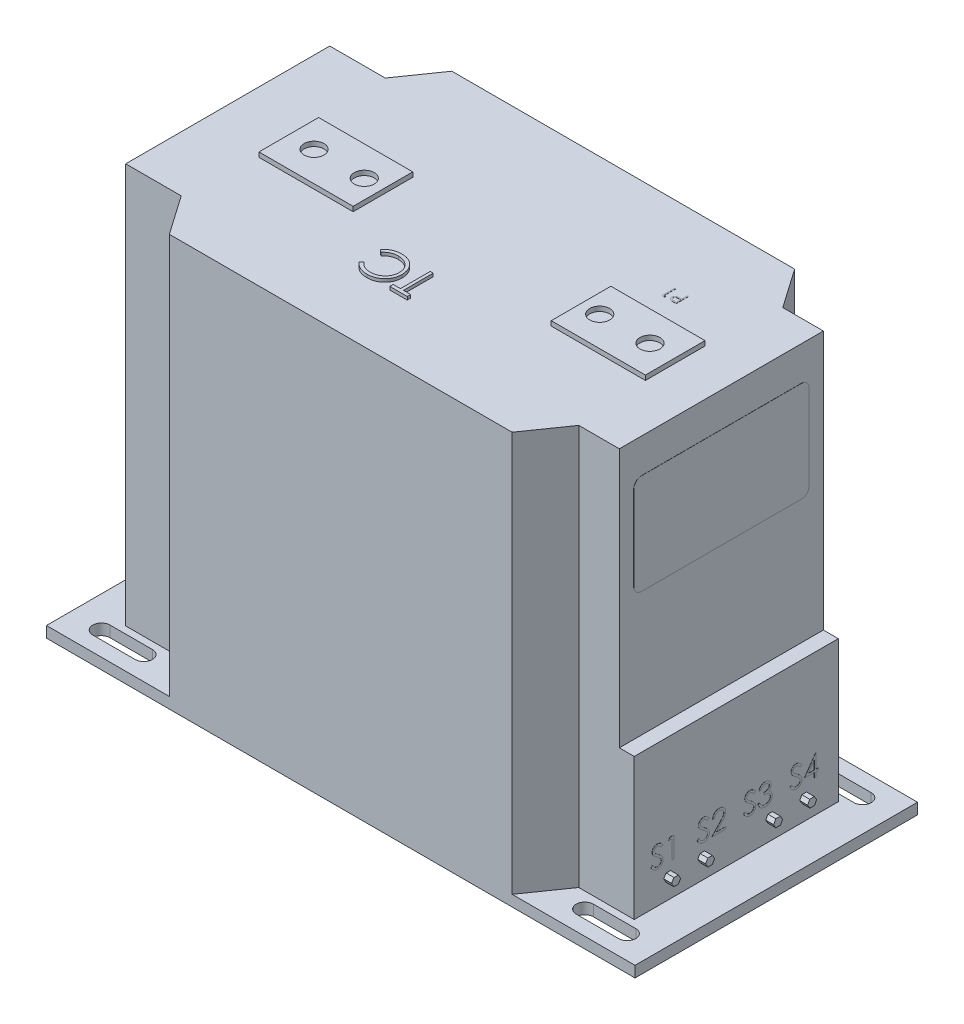
SolidWorks part; units mm, degrees
ref_plane "Alzado" through (0, 0, 0) normal (0, 0, 1) x (1, 0, 0)
ref_plane "Planta" through (0, 0, 0) normal (0, 1, 0) x (1, 0, 0)
ref_plane "Vista lateral" through (0, 0, 0) normal (1, 0, 0) x (0, 0, -1)
sketch "Croquis1" plane through (0, 0, 0) normal (0, 1, 0) x (1, 0, 0)
  line L1 (-187.5, 90) -> (187.5, 90)
  line L2 (-187.5, 90) -> (-187.5, -90)
  line L3 (-187.5, -90) -> (187.5, -90)
  line L4 (187.5, 90) -> (187.5, -90)
  line L5 (-187.5, 90) -> (187.5, -90) construction
  line L6 (-187.5, -90) -> (187.5, 90) construction
  point P0 (0, 0)
  dimension "D1" = 375
  dimension "D2" = 180
extrude "Saliente-Extruir1" add sketch "Croquis1" along normal blind 262
sketch "Croquis2" plane through (0, 262, 0) normal (0, 1, 0) x (1, 0, 0)
  line L0 (0, 0) -> (75, 0) construction
  line L1 (75, 0) -> (107, 0) construction
  line L2 (63.1078, 19) -> (63.1078, -19)
  line L3 (63.1078, -19) -> (123.1078, -19)
  line L4 (123.1078, -19) -> (123.1078, 19)
  line L5 (123.1078, 19) -> (63.1078, 19)
  line L6 (0, 0) -> (0, -29.2326) construction
  line L7 (-75, 0) -> (-107, 0) construction
  line L8 (-123.1078, 19) -> (-63.1078, 19)
  line L9 (-123.1078, -19) -> (-123.1078, 19)
  line L10 (-63.1078, -19) -> (-123.1078, -19)
  line L11 (-63.1078, 19) -> (-63.1078, -19)
  circle A0 centre (75, 0) radius 6.35
  circle A1 centre (107, 0) radius 6.35
  circle A2 centre (-107, 0) radius 6.35
  circle A3 centre (-75, 0) radius 6.35
  dimension "D2" = 12.7
  dimension "D3" = 12.7
  dimension "D1" = 75
  dimension "D4" = 32
  dimension "D5" = 38
  dimension "D6" = 60
  dimension "D7" = 19
extrude "Saliente-Extruir2" add sketch "Croquis2" along normal blind 3
sketch "Croquis3" plane through (0, 262, 0) normal (0, 1, 0) x (1, 0, 0)
  line L0 (0, 0) -> (0, 90) construction
  line L1 (187.5, 90) -> (-187.5, 90) construction
  line L2 (167.5, 75) -> (140.5, 75) construction
  line L3 (167.5, 69.5) -> (140.5, 69.5)
  line L4 (167.5, 80.5) -> (140.5, 80.5)
  line L5 (0, 0) -> (187.5, 0) construction
  line L6 (187.5, -90) -> (187.5, 90) construction
  line L7 (-167.5, 75) -> (-140.5, 75) construction
  line L8 (-167.5, 69.5) -> (-140.5, 69.5)
  line L9 (-167.5, 80.5) -> (-140.5, 80.5)
  line L10 (-167.5, -75) -> (-140.5, -75) construction
  line L11 (-167.5, -69.5) -> (-140.5, -69.5)
  line L12 (-167.5, -80.5) -> (-140.5, -80.5)
  line L13 (167.5, -75) -> (140.5, -75) construction
  line L14 (167.5, -69.5) -> (140.5, -69.5)
  line L15 (167.5, -80.5) -> (140.5, -80.5)
  line L16 (-126.6467, 65) -> (-109.1945, 90)
  line L17 (-162, 65) -> (-126.6467, 65)
  line L18 (-162, 65) -> (-162, -65)
  line L19 (-162, -65) -> (-126.6467, -65)
  line L20 (162, 65) -> (162, -65)
  line L21 (-162, 65) -> (162, -65) construction
  line L22 (-162, -65) -> (162, 65) construction
  line L23 (-126.6467, -65) -> (-109.1945, -90)
  line L24 (-187.5, -90) -> (187.5, -90) construction
  line L25 (126.6467, -65) -> (109.1945, -90)
  line L26 (126.6467, 65) -> (109.1945, 90)
  line L27 (126.6467, 65) -> (162, 65)
  line L28 (126.6467, -65) -> (162, -65)
  arc A0 (167.5, 69.5) -> (167.5, 80.5) centre (167.5, 75) ccw
  arc A1 (140.5, 80.5) -> (140.5, 69.5) centre (140.5, 75) ccw
  arc A2 (-167.5, 69.5) -> (-167.5, 80.5) centre (-167.5, 75) cw
  arc A3 (-140.5, 80.5) -> (-140.5, 69.5) centre (-140.5, 75) cw
  arc A4 (-167.5, -69.5) -> (-167.5, -80.5) centre (-167.5, -75) ccw
  arc A5 (-140.5, -80.5) -> (-140.5, -69.5) centre (-140.5, -75) ccw
  arc A6 (167.5, -69.5) -> (167.5, -80.5) centre (167.5, -75) cw
  arc A7 (140.5, -80.5) -> (140.5, -69.5) centre (140.5, -75) cw
  point P7 (154, 75)
  point P17 (-154, 75)
  point P24 (-154, -75)
  point P31 (154, -75)
  line M16 (187.5, -90) -> (187.5, 90)
  line M17 (187.5, 90) -> (-187.5, 90)
  line M18 (-187.5, 90) -> (-187.5, -90)
  line M19 (-187.5, -90) -> (187.5, -90)
  dimension "D1" = 75
  dimension "D2" = 167.5
  dimension "D3" = 27
  dimension "D4" = 11
  dimension "D5" = 162
  dimension "D6" = 130
extrude "Cortar-Extruir1" cut sketch "Croquis3" against normal blind 255 contours L23 L19 L18 L17 L16 A5 L12 A4 L11 L9 A3 L8 A2 M17 M18 M19 | L28 L25 L26 L27 L20 A1 L4 A0 L3 L15 A7 L14 A6 M19 M16 M17
sketch "Croquis4" plane through (0, 262, 0) normal (0, 1, 0) x (1, 0, 0)
  line L0 (-167.5, 75) -> (-140.5, 75) construction
  line L1 (-167.5, 80.5) -> (-140.5, 80.5)
  line L2 (-167.5, 69.5) -> (-140.5, 69.5)
  line L3 (-167.5, -75) -> (-140.5, -75) construction
  line L4 (-167.5, -69.5) -> (-140.5, -69.5)
  line L5 (-167.5, -80.5) -> (-140.5, -80.5)
  line L6 (140.5, 75) -> (167.5, 75) construction
  line L7 (140.5, 80.5) -> (167.5, 80.5)
  line L8 (140.5, 69.5) -> (167.5, 69.5)
  line L9 (140.5, -75) -> (167.5, -75) construction
  line L10 (140.5, -69.5) -> (167.5, -69.5)
  line L11 (140.5, -80.5) -> (167.5, -80.5)
  arc A0 (-167.5, 80.5) -> (-167.5, 69.5) centre (-167.5, 75) ccw
  arc A1 (-140.5, 69.5) -> (-140.5, 80.5) centre (-140.5, 75) ccw
  arc A2 (-167.5, -69.5) -> (-167.5, -80.5) centre (-167.5, -75) ccw
  arc A3 (-140.5, -80.5) -> (-140.5, -69.5) centre (-140.5, -75) ccw
  arc A4 (140.5, 80.5) -> (140.5, 69.5) centre (140.5, 75) ccw
  arc A5 (167.5, 69.5) -> (167.5, 80.5) centre (167.5, 75) ccw
  arc A6 (140.5, -69.5) -> (140.5, -80.5) centre (140.5, -75) ccw
  arc A7 (167.5, -80.5) -> (167.5, -69.5) centre (167.5, -75) ccw
  point P4 (-154, 75)
  point P13 (-154, -75)
  point P22 (154, 75)
  point P31 (154, -75)
  dimension "D1" = 11
  dimension "D2" = 11
  dimension "D3" = 11
  dimension "D4" = 11
extrude "Cortar-Extruir2" cut sketch "Croquis4" against normal blind 277
sketch "Croquis5" plane through (162, 0, 0) normal (1, 0, 0) x (0, 0, -1)
  line L0 (-65, 7) -> (-65, 97)
  line L1 (-65, 7) -> (-65, 262) construction
  line L2 (-65, 97) -> (65, 97)
  line L3 (65, 7) -> (65, 262) construction
  line L4 (65, 97) -> (65, 7)
  line L5 (65, 7) -> (-65, 7)
  line L6 (-65, 97) -> (-65, 262)
  line L7 (-65, 262) -> (65, 262)
  line L8 (65, 262) -> (65, 97)
  line M3 (65, 262) -> (-65, 262)
  line M4 (-65, 262) -> (-65, 7)
  line M6 (65, 7) -> (65, 262)
  dimension "D1" = 90
extrude "Cortar-Extruir3" cut sketch "Croquis5" against normal blind 9.5 contours L2 M4 M6 M3
sketch "Croquis6" plane through (162, 0, 0) normal (1, 0, 0) x (0, 0, -1)
  line L0 (0, 0) -> (0, 20) construction
  line L1 (0, 20) -> (21.6667, 20) construction
  line L3 (24.5534, 20) -> (23.11, 22.5)
  line L4 (23.11, 22.5) -> (20.2233, 22.5)
  line L5 (20.2233, 22.5) -> (18.7799, 20)
  line L6 (18.7799, 20) -> (20.2233, 17.5)
  line L7 (20.2233, 17.5) -> (23.11, 17.5)
  line L8 (23.11, 17.5) -> (24.5534, 20)
  line L9 (44.8571, 17.5461) -> (46.222, 20.0897)
  line L10 (46.222, 20.0897) -> (44.7016, 22.5437)
  line L11 (44.7016, 22.5437) -> (41.8163, 22.4539)
  line L12 (41.8163, 22.4539) -> (40.4513, 19.9103)
  line L13 (40.4513, 19.9103) -> (41.9717, 17.4563)
  line L14 (41.9717, 17.4563) -> (44.8571, 17.5461)
  line L15 (-41.9717, 17.4563) -> (-44.8571, 17.5461)
  line L16 (-40.4513, 19.9103) -> (-41.9717, 17.4563)
  line L17 (-41.8163, 22.4539) -> (-40.4513, 19.9103)
  line L18 (-44.7016, 22.5437) -> (-41.8163, 22.4539)
  line L19 (-46.222, 20.0897) -> (-44.7016, 22.5437)
  line L20 (-44.8571, 17.5461) -> (-46.222, 20.0897)
  line L21 (-23.11, 17.5) -> (-24.5534, 20)
  line L22 (-20.2233, 17.5) -> (-23.11, 17.5)
  line L23 (-18.7799, 20) -> (-20.2233, 17.5)
  line L24 (-20.2233, 22.5) -> (-18.7799, 20)
  line L25 (-23.11, 22.5) -> (-20.2233, 22.5)
  line L26 (-24.5534, 20) -> (-23.11, 22.5)
  circle A0 centre (21.6667, 20) radius 2.5 construction
  circle A1 centre (43.3367, 20) radius 2.5 construction
  circle A2 centre (-43.3367, 20) radius 2.5 construction
  circle A3 centre (-21.6667, 20) radius 2.5 construction
  dimension "D1" = 20
  dimension "D2" = 5
  dimension "D3" = 5
  dimension "D4" = 21.6667
  dimension "D5" = 21.67
extrude "Saliente-Extruir3" add sketch "Croquis6" along normal blind 5
sketch "Croquis7" plane through (162, 0, 0) normal (1, 0, 0) x (0, 0, -1)
  text T0 "\r\n\r\n\r\n  S1  S2  S3  S4" font "Century Gothic" height in points 50
extrude "Saliente-Extruir4" add sketch "Croquis7" along normal blind 0.1
sketch "Croquis8" plane through (152.5, 0, 0) normal (1, 0, 0) x (0, 0, -1)
  line L1 (-50.8517, 240.1495) -> (50.8517, 240.1495)
  line L2 (-55.8517, 235.1495) -> (-55.8517, 181.3189)
  line L3 (-50.8517, 176.3189) -> (50.8517, 176.3189)
  line L4 (55.8517, 235.1495) -> (55.8517, 181.3189)
  line L5 (-55.8517, 240.1495) -> (55.8517, 176.3189) construction
  line L6 (-55.8517, 176.3189) -> (55.8517, 240.1495) construction
  arc A0 (50.8517, 240.1495) -> (55.8517, 235.1495) centre (50.8517, 235.1495) cw
  arc A1 (50.8517, 176.3189) -> (55.8517, 181.3189) centre (50.8517, 181.3189) ccw
  arc A2 (-55.8517, 181.3189) -> (-50.8517, 176.3189) centre (-50.8517, 181.3189) ccw
  arc A3 (-50.8517, 240.1495) -> (-55.8517, 235.1495) centre (-50.8517, 235.1495) ccw
  point P0 (0, 208.2342)
  dimension "D1" = 5
extrude "Saliente-Extruir5" add sketch "Croquis8" along normal blind 0.1
sketch "Croquis9" plane through (-162, 0, 0) normal (-1, 0, 0) x (0, 0, 1)
  circle A0 centre (43.7616, 21.8867) radius 4.75
  dimension "D1" = 9.5
extrude "Saliente-Extruir6" add sketch "Croquis9" along normal blind 5
sketch "Croquis11" plane through (0, 262, 0) normal (0, 1, 0) x (1, 0, 0)
  line L0 (131.245, 41.1105) -> (46.938, 41.1105) construction
  line L1 (46.938, 41.1105) -> (-140.5419, 41.1105) construction
  text T0 "             P1                      " font "Century Gothic" height in points 30
extrude "Saliente-Extruir7" add sketch "Croquis11" along normal blind 0.1
sketch "Croquis12" plane through (0, 262, 0) normal (0, 1, 0) x (1, 0, 0)
  line L1 (108.9995, -29.346) -> (-107.7095, -29.346) construction
  text T0 "             TC" font "Century Gothic" height in points 80
extrude "Saliente-Extruir8" add sketch "Croquis12" along normal blind 2
ref_plane "Plano1" through (0, 0, 0) normal (0, 0, 1) x (1, 0, 0)
